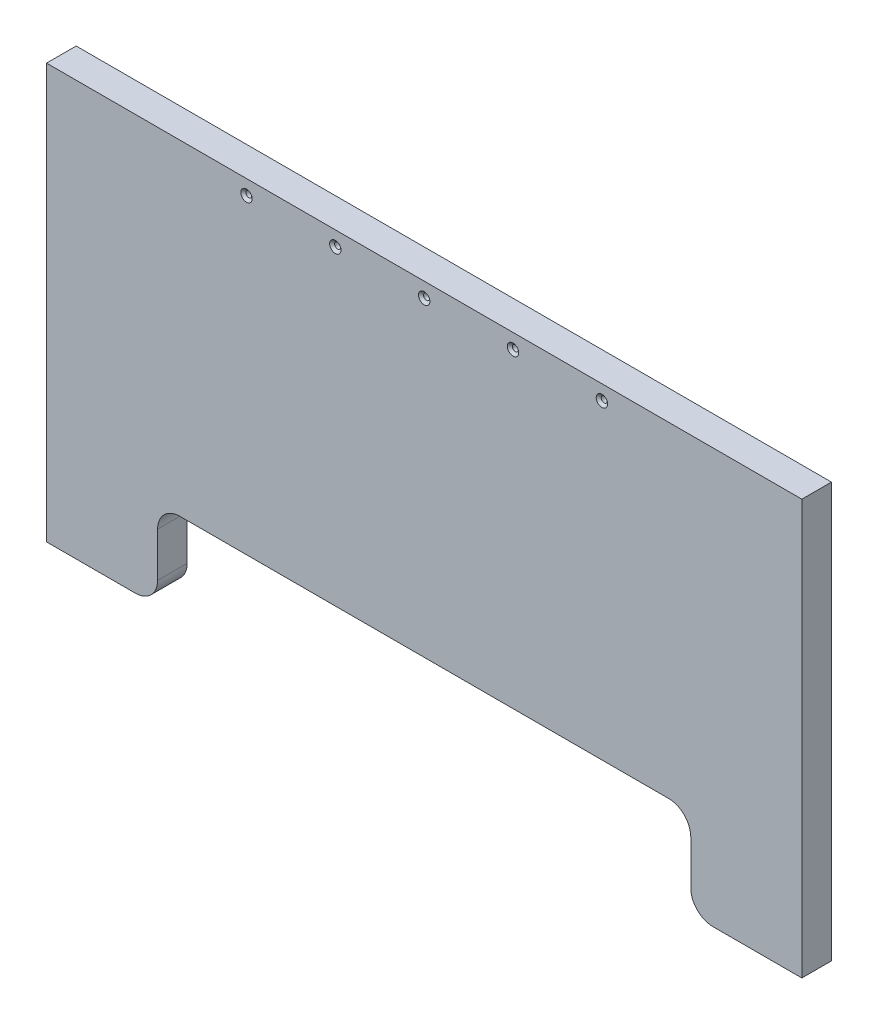
SolidWorks part; units mm, degrees
ref_plane "Front Plane" through (0, 0, 0) normal (0, 0, 1) x (1, 0, 0)
ref_plane "Top Plane" through (0, 0, 0) normal (0, 1, 0) x (1, 0, 0)
ref_plane "Right Plane" through (0, 0, 0) normal (1, 0, 0) x (0, 0, -1)
sketch "Sketch1" plane through (0, 0, 0) normal (0, 0, 1) x (1, 0, 0)
  line L0 (-323.85, 279.4) -> (323.85, 279.4)
  line L1 (323.85, 279.4) -> (323.85, -76.2)
  line L2 (323.85, -76.2) -> (228.6, -76.2)
  line L3 (228.6, -76.2) -> (228.6, 0)
  line L4 (228.6, 0) -> (-228.6, 0)
  line L5 (0, 0) -> (0, 279.4) construction
  line L6 (-228.6, -76.2) -> (-228.6, 0)
  line L7 (-323.85, -76.2) -> (-228.6, -76.2)
  line L8 (-323.85, 279.4) -> (-323.85, -76.2)
  dimension "D1" = 76.2
  dimension "D2" = 647.7
  dimension "D3" = 457.2
  dimension "D4" = 279.4
extrude "Boss-Extrude1" add sketch "Sketch1" along normal blind 25.4
fillet "Fillet1" radius 19.05 4 edges at (228.6, 0, 12.7) (228.6, -76.2, 12.7) (-228.6, -76.2, 12.7) (-228.6, 0, 12.7)
hole_wizard "CSK for #10 Flat Head Machine Screw (100)1" positions "Sketch2" profile "Sketch3" countersink size "#10" standard "ANSI Inch" end condition through all
sketch "Sketch2" plane through (0, 0, 25.4) normal (0, 0, 1) x (1, 0, 0)
  line L2 (0, 266.7) -> (0, 279.4)
  line L3 (323.85, 279.4) -> (-323.85, 279.4) construction
  point P5 (0, 266.7)
  point P19 (76.2, 266.7)
  point P20 (152.4, 266.7)
  point P24 (-76.2, 266.7)
  point P25 (-152.4, 266.7)
  dimension "D1" = 12.7
  dimension "D2" = 3
  dimension "D3" = 3
sketch "Sketch3" plane through (0, 266.7, 25.4) normal (1, 0, 0) x (0, -1, 0)
  line L0 (0, 0) -> (0, 25.4)
  line L1 (0, 25.4) -> (2.5527, 25.4)
  line L2 (2.5527, 25.4) -> (2.5527, 1.9608)
  line L3 (2.5527, 1.9608) -> (4.8895, 0)
  line L5 (4.8895, 0) -> (0, 0)
  line L6 (-2.5527, 1.9608) -> (-4.8895, 0) construction
  line L11 (0, -6.35) -> (0, 107.95) construction
  dimension "Thru Hole Dia." = 5.1054
  dimension "Thru Hole Depth" = 25.4
  dimension "Near C'Sink Dia." = 9.779
  dimension "Near C'Sink Angle" = 100
